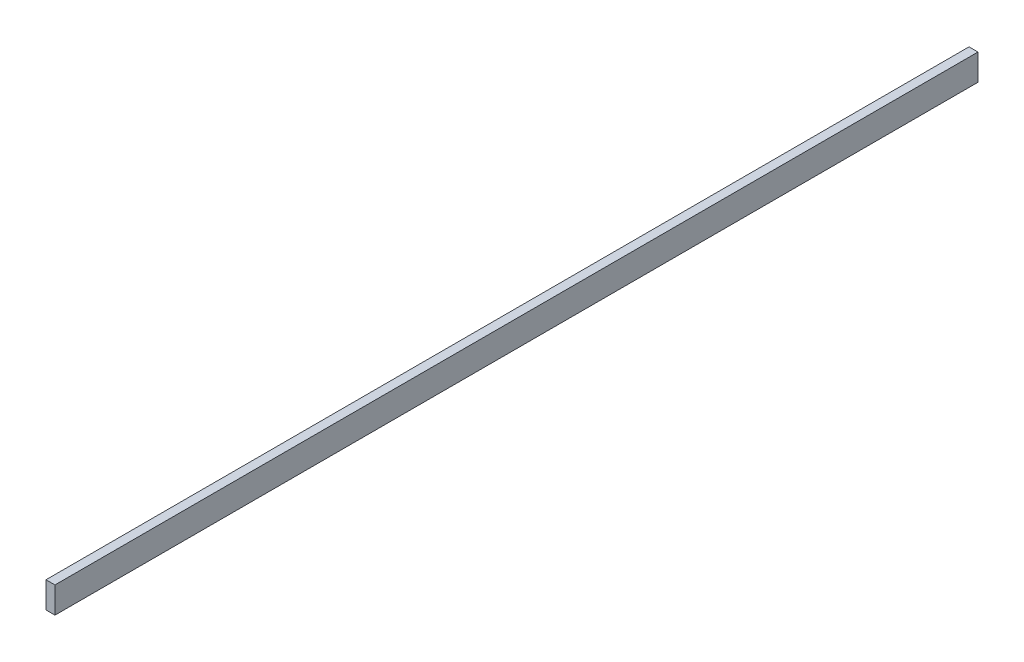
SolidWorks part; units mm, degrees
ref_plane "Front Plane" through (0, 0, 0) normal (0, 0, 1) x (1, 0, 0)
ref_plane "Top Plane" through (0, 0, 0) normal (0, 1, 0) x (1, 0, 0)
ref_plane "Right Plane" through (0, 0, 0) normal (1, 0, 0) x (0, 0, -1)
sketch "Sketch1" plane through (0, 0, 0) normal (0, 0, 1) x (1, 0, 0)
  line L0 (6482.8372, 4654.3078) -> (6482.8372, 4617.1748)
  line L1 (6495.5372, 4654.3078) -> (6495.5372, 4617.1748)
  line L2 (6495.5372, 4654.3078) -> (6482.8372, 4654.3078)
  line L3 (6495.5372, 4617.1748) -> (6482.8372, 4617.1748)
extrude "Boss-Extrude1" add sketch "Sketch1" along normal blind 1308.1
